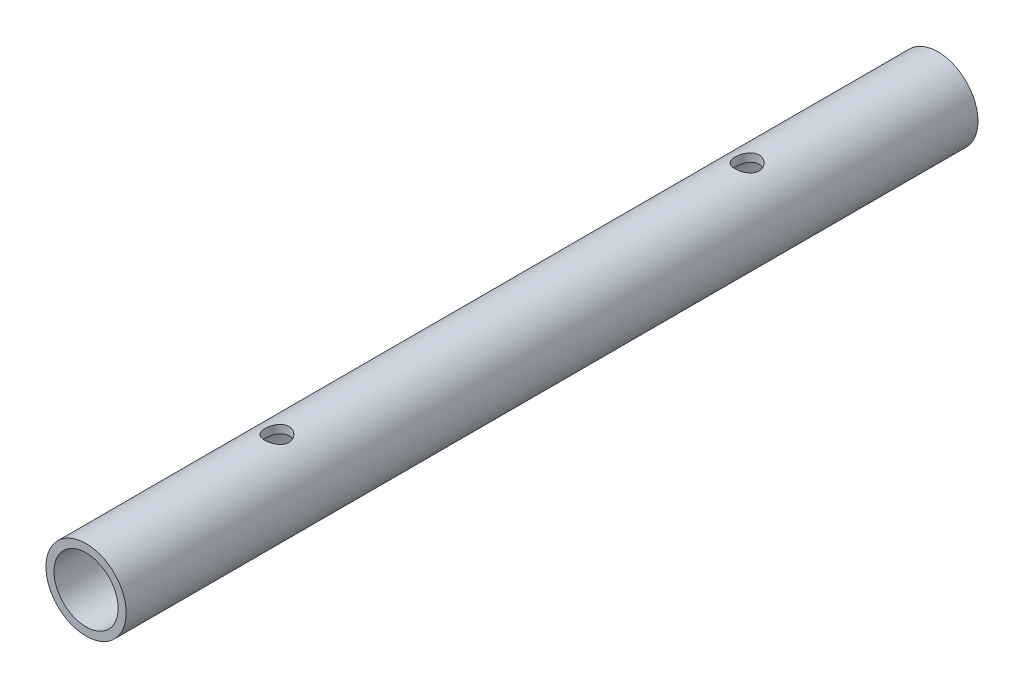
SolidWorks part; units mm, degrees
ref_plane "Plan de face" through (0, 0, 0) normal (0, 0, 1) x (1, 0, 0)
ref_plane "Plan de dessus" through (0, 0, 0) normal (0, 1, 0) x (1, 0, 0)
ref_plane "Plan de droite" through (0, 0, 0) normal (1, 0, 0) x (0, 0, -1)
sketch "Sketch1" plane through (0, 0, 0) normal (0, 0, 1) x (1, 0, 0)
  circle A0 centre (0, 0) radius 5
extrude "Boss-Extrude1" add sketch "Sketch1" along normal blind 106.148
sketch "Sketch2" plane through (0, 0, 106.148) normal (0, 0, 1) x (1, 0, 0)
  circle A0 centre (0, 0) radius 4
extrude "Cut-Extrude1" cut sketch "Sketch2" against normal up to next
sketch "Sketch5" plane through (0, 0, 0) normal (0, 1, 0) x (1, 0, 0)
  circle A0 centre (0, -23.777) radius 1.5
  circle A1 centre (0, -82.371) radius 1.5
  dimension "D1" = 23.777
  dimension "D2" = 82.371
extrude "Cut-Extrude2" cut sketch "Sketch5" against normal through all and the other way through all
